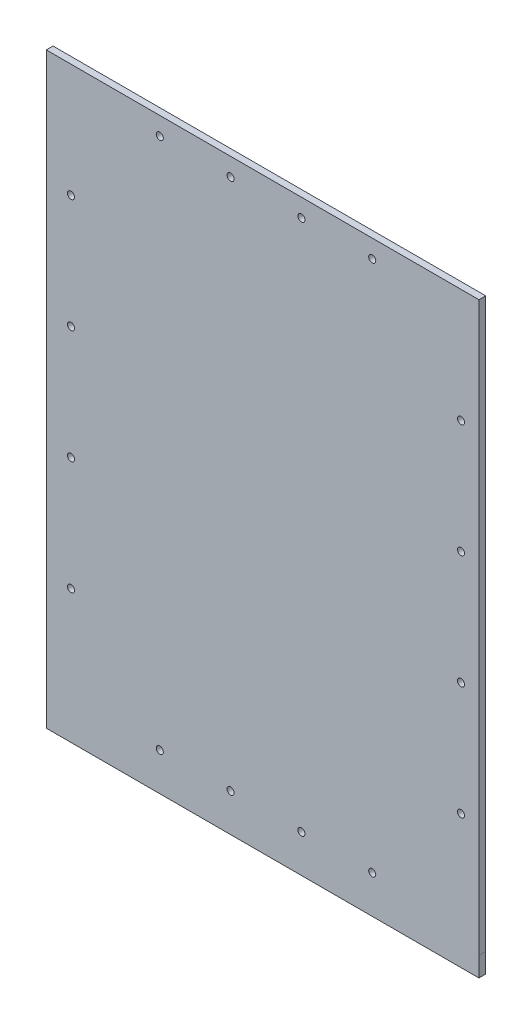
SolidWorks part; units mm, degrees
ref_plane "前基準面" through (0, 0, 0) normal (0, 0, 1) x (1, 0, 0)
ref_plane "上基準面" through (0, 0, 0) normal (0, 1, 0) x (1, 0, 0)
ref_plane "右基準面" through (0, 0, 0) normal (1, 0, 0) x (0, 0, -1)
sketch "草圖1" plane through (0, 0, 0) normal (0, 0, 1) x (1, 0, 0)
  line L1 (152.775, -202.775) -> (-152.775, -202.775)
  line L2 (152.775, -202.775) -> (152.775, 202.775)
  line L3 (152.775, 202.775) -> (-152.775, 202.775)
  line L4 (-152.775, -202.775) -> (-152.775, 202.775)
  line L5 (152.775, -202.775) -> (-152.775, 202.775) construction
  line L6 (152.775, 202.775) -> (-152.775, -202.775) construction
  point P0 (0, 0)
  dimension "D1" = 305.55
  dimension "D2" = 405.55
extrude "填料-伸長1" add sketch "草圖1" along normal blind 4.75
sketch "草圖3" plane through (0, 0, 4.75) normal (0, 0, 1) x (1, 0, 0)
  line L0 (152.775, 202.775) -> (140.075, 202.775) construction
  line L1 (152.775, 202.775) -> (-152.775, 202.775) construction
  line L2 (140.075, 202.775) -> (140.075, 198.025) construction
  line L3 (140.075, 198.025) -> (140.075, 117.865) construction
  line L4 (140.075, 117.865) -> (140.075, 37.705) construction
  line L5 (140.075, 37.705) -> (140.075, -42.455) construction
  line L6 (140.075, -42.455) -> (140.075, -122.615) construction
  circle A0 centre (140.075, 37.705) radius 2.5
  circle A1 centre (140.075, 117.865) radius 2.5
  circle A2 centre (140.075, -42.455) radius 2.5
  circle A3 centre (140.075, -122.615) radius 2.5
  dimension "D7" = 5
  dimension "D8" = 5
  dimension "D9" = 5
  dimension "D10" = 5
  dimension "D1" = 12.7
  dimension "D2" = 4.75
  dimension "D3" = 80.16
  dimension "D4" = 80.16
  dimension "D5" = 80.16
  dimension "D6" = 80.16
extrude "除料-伸長1" cut sketch "草圖3" against normal blind 10
sketch "草圖5" plane through (0, 0, 4.75) normal (0, 0, 1) x (1, 0, 0)
  line L0 (-152.775, 202.775) -> (-148.025, 202.775) construction
  line L1 (152.775, 202.775) -> (-152.775, 202.775) construction
  line L2 (-148.025, 202.775) -> (-135.325, 202.775) construction
  line L3 (-135.325, 202.775) -> (-135.325, 198.025) construction
  line L4 (-135.325, 198.025) -> (-135.325, 117.865) construction
  line L5 (-135.325, 117.865) -> (-135.325, 37.705) construction
  line L6 (-135.325, 37.705) -> (-135.325, -42.455) construction
  line L7 (-135.325, -42.455) -> (-135.325, -122.615) construction
  circle A0 centre (-135.325, -122.615) radius 2.5
  circle A1 centre (-135.325, -42.455) radius 2.5
  circle A2 centre (-135.325, 37.705) radius 2.5
  circle A3 centre (-135.325, 117.865) radius 2.5
  dimension "D8" = 5
  dimension "D9" = 5
  dimension "D10" = 5
  dimension "D11" = 5
  dimension "D1" = 4.75
  dimension "D2" = 12.7
  dimension "D3" = 4.75
  dimension "D4" = 80.16
  dimension "D5" = 80.16
  dimension "D6" = 80.16
  dimension "D7" = 80.16
extrude "除料-伸長3" cut sketch "草圖5" against normal blind 10
sketch "草圖6" plane through (0, 0, 0) normal (0, 0, -1) x (-1, 0, 0)
  line L0 (-152.775, 202.775) -> (-127.375, 202.775) construction
  line L1 (-152.775, 202.775) -> (152.775, 202.775) construction
  line L2 (-127.375, 202.775) -> (-127.375, 190.075) construction
  line L3 (-127.375, 190.075) -> (-127.375, 185.325) construction
  line L4 (-127.375, 185.325) -> (-77.375, 185.325) construction
  line L5 (-77.375, 185.325) -> (-27.375, 185.325) construction
  line L6 (-27.375, 185.325) -> (22.625, 185.325) construction
  line L7 (22.625, 185.325) -> (72.625, 185.325) construction
  circle A0 centre (22.625, 185.325) radius 2.5
  circle A1 centre (72.625, 185.325) radius 2.5
  circle A2 centre (-77.375, 185.325) radius 2.5
  circle A3 centre (-27.375, 185.325) radius 2.5
  dimension "D8" = 5
  dimension "D9" = 5
  dimension "D10" = 5
  dimension "D11" = 5
  dimension "D1" = 25.4
  dimension "D2" = 12.7
  dimension "D3" = 4.75
  dimension "D4" = 50
  dimension "D5" = 50
  dimension "D6" = 50
  dimension "D7" = 50
extrude "除料-伸長4" cut sketch "草圖6" against normal blind 10
sketch "草圖7" plane through (0, 0, 0) normal (0, 0, -1) x (-1, 0, 0)
  line L0 (-152.775, -202.775) -> (-152.775, -190.075) construction
  line L1 (-152.775, -202.775) -> (-152.775, 202.775) construction
  line L2 (-152.775, -190.075) -> (-127.375, -190.075) construction
  line L3 (-127.375, -190.075) -> (-77.375, -190.075) construction
  line L4 (-77.375, -190.075) -> (-27.375, -190.075) construction
  line L5 (-27.375, -190.075) -> (22.625, -190.075) construction
  line L6 (22.625, -190.075) -> (72.625, -190.075) construction
  circle A0 centre (-77.375, -190.075) radius 2.5
  circle A1 centre (-27.375, -190.075) radius 2.5
  circle A2 centre (22.625, -190.075) radius 2.5
  circle A3 centre (72.625, -190.075) radius 2.5
  dimension "D7" = 5
  dimension "D8" = 5
  dimension "D9" = 5
  dimension "D10" = 5
  dimension "D1" = 12.7
  dimension "D2" = 25.4
  dimension "D3" = 50
  dimension "D4" = 50
  dimension "D5" = 50
  dimension "D6" = 50
extrude "除料-伸長5" cut sketch "草圖7" against normal blind 10
sketch "草圖8" plane through (0, 0, 4.75) normal (0, 0, 1) x (1, 0, 0)
  line L0 (152.775, -202.775) -> (152.775, 202.775) construction
  line L1 (-152.775, 202.775) -> (152.775, 202.775)
  line L2 (-152.775, 202.775) -> (-152.775, 198.025)
  line L3 (-152.775, 198.025) -> (152.775, 198.025)
  line L4 (152.775, 202.775) -> (152.775, 198.025)
  dimension "D1" = 4.75
split "分割1" trim tools "草圖8" bodies to split 106 resulting bodies 107
sketch "草圖9" plane through (0, 0, 0) normal (0, 0, 1) x (1, 0, 0)
  line L1 (-152.775, -202.775) -> (152.725, -202.775)
  line L2 (-152.775, -202.775) -> (-152.775, -216.775)
  line L3 (-152.775, -216.775) -> (152.725, -216.775)
  line L4 (152.725, -202.775) -> (152.725, -216.775)
  dimension "D1" = 305.5
  dimension "D2" = 14
extrude "填料-伸長2" add sketch "草圖9" along normal blind 4.75
